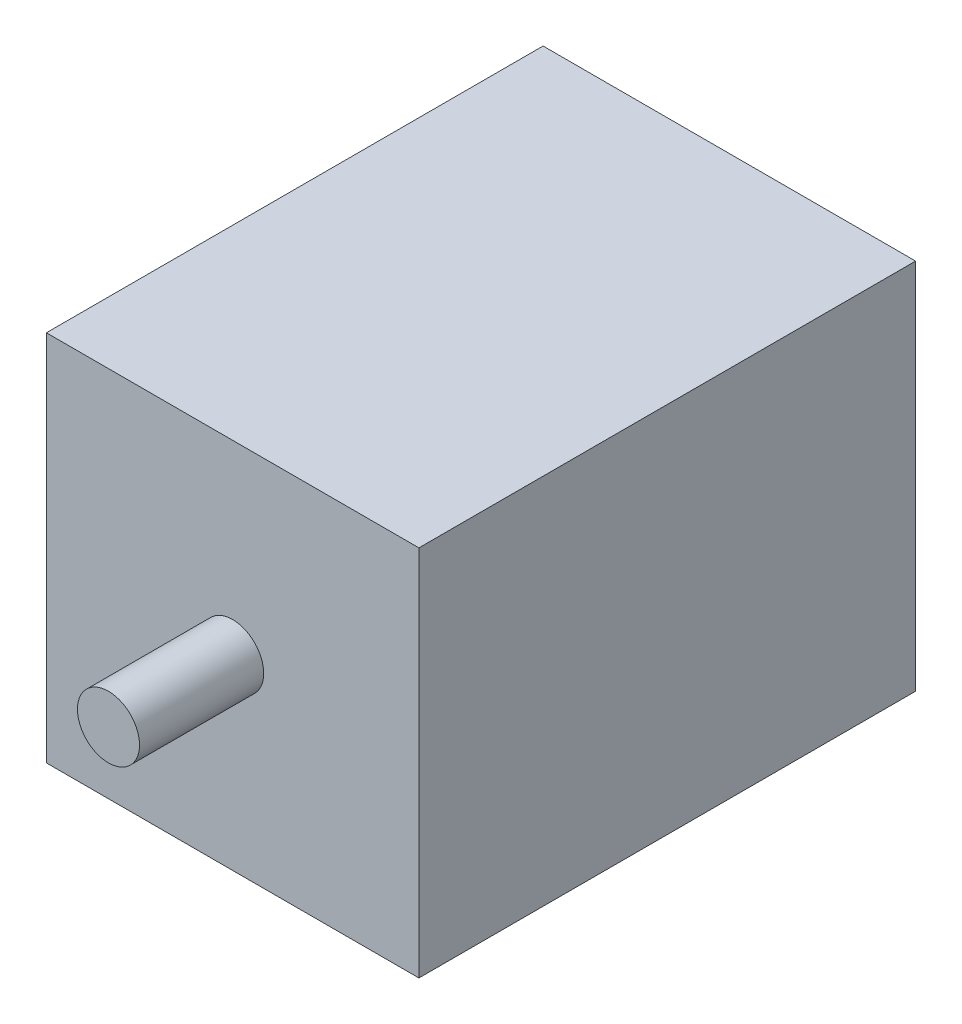
SolidWorks part; units mm, degrees
ref_plane "Front Plane" through (0, 0, 0) normal (0, 0, 1) x (1, 0, 0)
ref_plane "Top Plane" through (0, 0, 0) normal (0, 1, 0) x (1, 0, 0)
ref_plane "Right Plane" through (0, 0, 0) normal (1, 0, 0) x (0, 0, -1)
sketch "Sketch1" plane through (0, 0, 0) normal (0, 0, 1) x (1, 0, 0)
  line L5 (-19.05, -19.05) -> (19.05, -19.05)
  line L6 (-19.05, -19.05) -> (-19.05, 19.05)
  line L7 (-19.05, 19.05) -> (19.05, 19.05)
  line L8 (19.05, -19.05) -> (19.05, 19.05)
  line L9 (-19.05, -19.05) -> (19.05, 19.05) construction
  line L10 (-19.05, 19.05) -> (19.05, -19.05) construction
  point P4 (0, 0)
  dimension "D1" = 38.1
  dimension "D2" = 38.1
extrude "Boss-Extrude1" add sketch "Sketch1" along normal mid plane 50.8
sketch "Sketch2" plane through (0, 0, 25.4) normal (0, 0, 1) x (1, 0, 0)
  circle A0 centre (0, 0) radius 3.175
  dimension "D1" = 6.35
extrude "Boss-Extrude2" add sketch "Sketch2" along normal blind 12.7
ref_plane "Plane1" through (0, 0, 31.75) normal (0, 0, 1) x (1, 0, 0)
